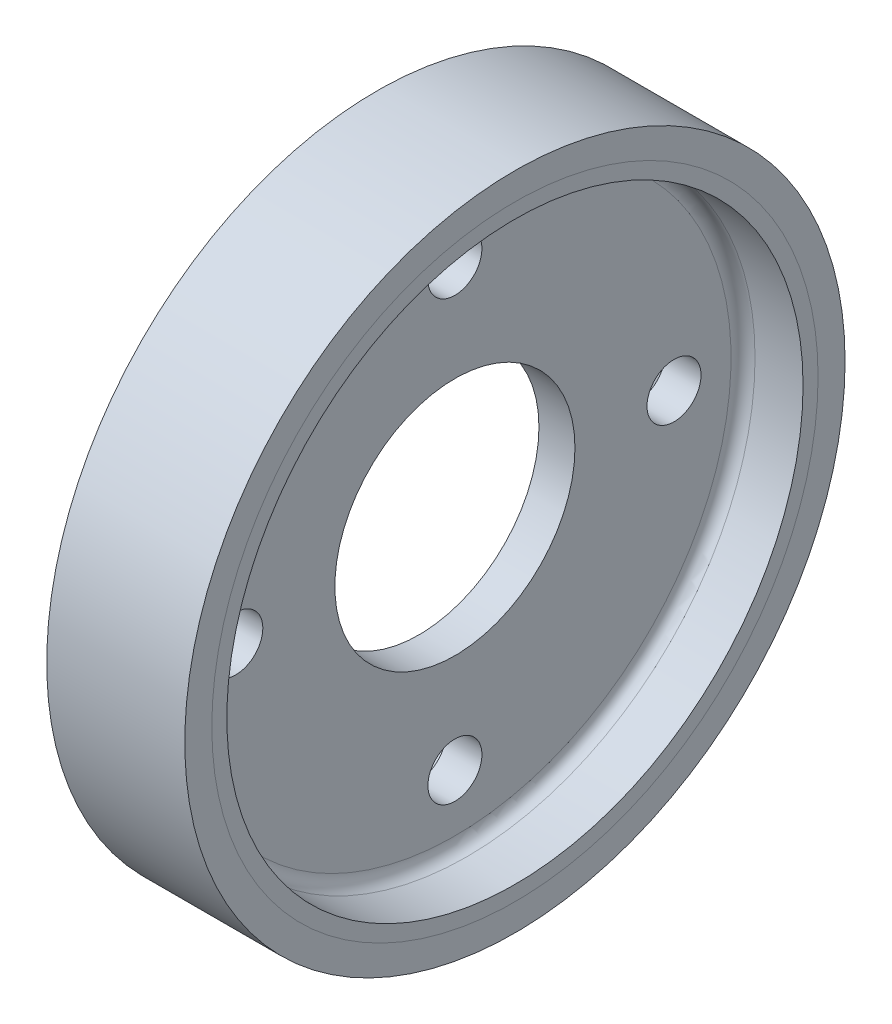
SolidWorks part; units mm, degrees
other "GEAR TOOTH "
material "Plain Carbon Steel"
ref_plane "Front Plane" through (0, 0, 0) normal (0, 0, 1) x (1, 0, 0)
ref_plane "Top Plane" through (0, 0, 0) normal (0, 1, 0) x (1, 0, 0)
ref_plane "Right Plane" through (0, 0, 0) normal (1, 0, 0) x (0, 0, -1)
sketch "Sketch1" plane through (0, 0, 0) normal (0, 0, 1) x (1, 0, 0)
  line L0 (0, 0) -> (-67.1842, 0) construction
  line L2 (0, 0) -> (-23, 0)
  line L3 (0, 0) -> (0, 50.5)
  line L4 (0, 50.5) -> (-23, 50.5)
  line L5 (-23, 0) -> (-23, 50.5)
  dimension "D1" = 23
  dimension "D2" = 101
revolve "Revolve1" add sketch "Sketch1" angle 360 about L0
sketch "Sketch2" plane through (0, 0, 0) normal (0, 0, 1) x (1, 0, 0)
  line L0 (0, 0) -> (-43.1244, 0) construction
  line L1 (0, -50.5) -> (0, 50.5) construction
  line L2 (-23, 50.5) -> (0, 50.5)
  line L3 (-23, 50.5) -> (-23, 55)
  line L4 (-23, 55) -> (0, 55)
  line L5 (0, 50.5) -> (0, 55)
  dimension "D1" = 4.5
revolve "Revolve2" add sketch "Sketch2" angle 360 about L0
sketch "Sketch3" plane through (0, 0, 0) normal (0, 0, 1) x (1, 0, 0)
  line L0 (0, 0) -> (-50.5133, 0) construction
  line L1 (0, 48) -> (-10, 48)
  line L2 (0, -50.5) -> (0, 50.5) construction
  line L3 (-10, 48) -> (-10, 20)
  line L4 (-10, 20) -> (-16, 20)
  line L5 (-16, 20) -> (-16, 44)
  line L6 (-16, 44) -> (-23, 44)
  line L7 (-23, 50.5) -> (-23, -50.5) construction
  line L8 (-23, 44) -> (-23, 0)
  line L9 (-23, 0) -> (0, 0)
  line L10 (0, 0) -> (0, 48)
  dimension "D1" = 88
  dimension "D2" = 40
  dimension "D3" = 96
  dimension "D4" = 7
  dimension "6" = 6
revolve "Cut-Revolve1" cut sketch "Sketch3" angle 360 about L0
hole_wizard "Ø9.0 (9) Diameter Hole1" positions "Sketch4" profile "Sketch5" hole size "Ø9.0" standard "ISO" end condition through all
sketch "Sketch4" plane through (-16, 0, 0) normal (-1, 0, 0) x (0, 0, 1)
  point P0 (0, 36.5)
  dimension "D1" = 36.5
sketch "Sketch5" plane through (-16, 36.5, 0) normal (0, 1, 0) x (0, 0, 1)
  line L0 (0, 0) -> (0, 16)
  line L1 (0, 16) -> (4.5, 16)
  line L2 (4.5, 16) -> (4.5, 0)
  line L5 (4.5, 0) -> (0, 0)
  line L11 (0, -6.35) -> (0, 107.95) construction
  dimension "Thru Hole Dia." = 9
  dimension "Thru Hole Depth" = 16
pattern_circular "CirPattern1" count 4 over 360 about axis through (0, 0, 0) along (1, 0, 0) of "Ø9.0 (9) Diameter Hole1"
fillet "Fillet1" radius 2 1 edges at (-10, 0, -48)
chamfer "Chamfer2" distance 1 angle 45 1 edges at (-23, 0, -44)
